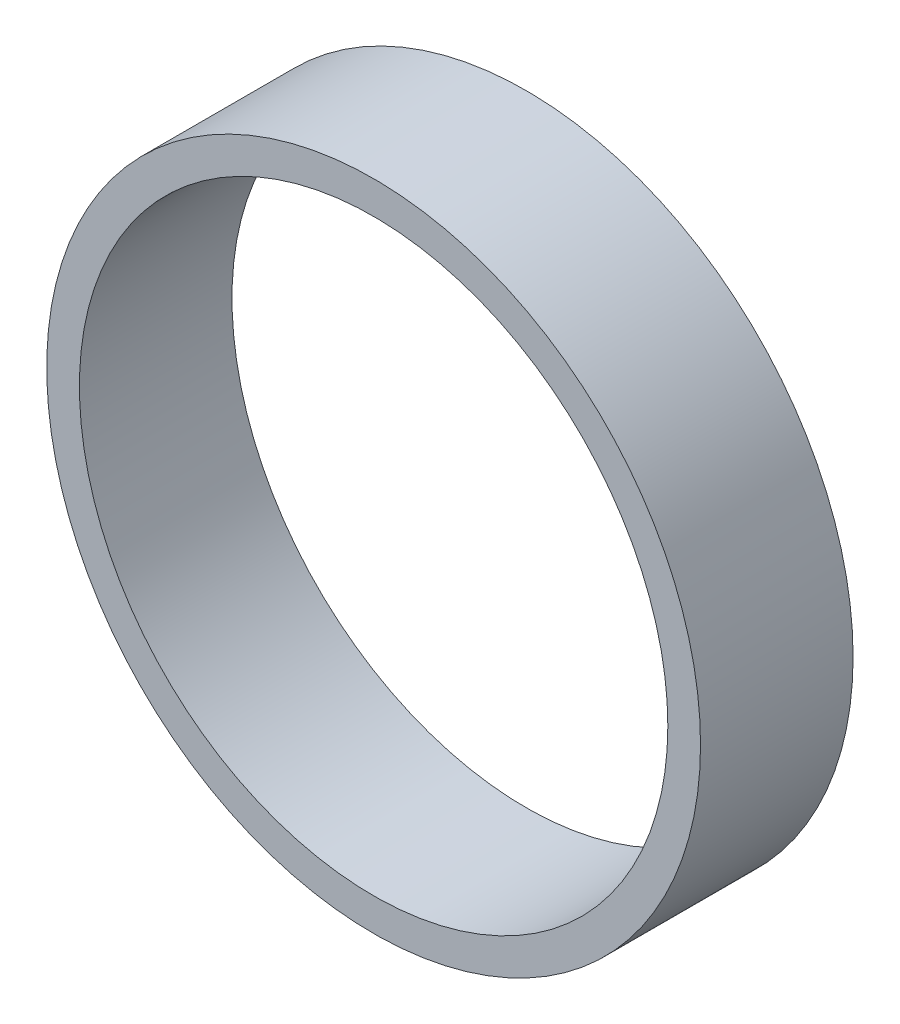
SolidWorks part; units mm, degrees
ref_plane "Front Plane" through (0, 0, 0) normal (0, 0, 1) x (1, 0, 0)
ref_plane "Top Plane" through (0, 0, 0) normal (0, 1, 0) x (1, 0, 0)
ref_plane "Right Plane" through (0, 0, 0) normal (1, 0, 0) x (0, 0, -1)
sketch "Sketch1" plane through (0, 0, 0) normal (0, 0, 1) x (1, 0, 0)
  circle A0 centre (0, 0) radius 15
  circle A1 centre (0, 0) radius 13.5
  dimension "D1" = 30
  dimension "D2" = 27
extrude "Boss-Extrude1" add sketch "Sketch1" along normal blind 7
